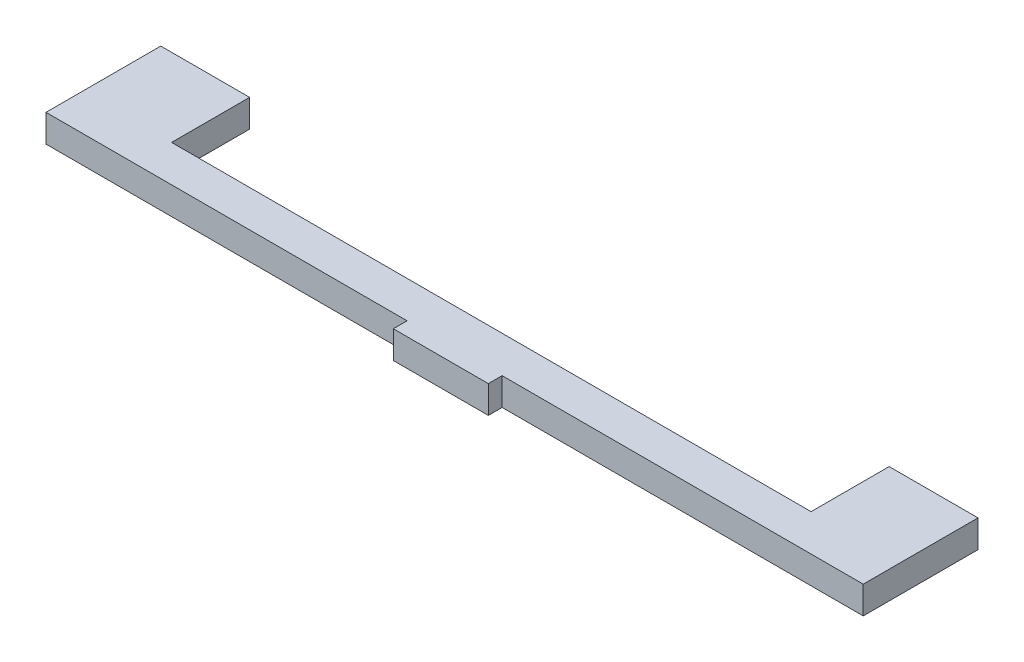
SolidWorks part; units mm, degrees
ref_plane "Front Plane" through (0, 0, 0) normal (0, 0, 1) x (1, 0, 0)
ref_plane "Top Plane" through (0, 0, 0) normal (0, 1, 0) x (1, 0, 0)
ref_plane "Right Plane" through (0, 0, 0) normal (1, 0, 0) x (0, 0, -1)
sketch "Sketch1" plane through (0, 0, 0) normal (0, 1, 0) x (1, 0, 0)
  line L0 (-9.9188, -12.9852) -> (10.7812, -12.9852)
  line L1 (10.7812, -12.9852) -> (10.7812, -9.9852)
  line L2 (10.7812, -9.9852) -> (89.4312, -9.9852)
  line L3 (89.4312, -9.9852) -> (89.4312, 15.0148)
  line L4 (89.4312, 15.0148) -> (70.0781, 15.0148)
  line L5 (70.0781, 15.0148) -> (70.0781, -1.9852)
  line L6 (70.0781, -1.9852) -> (-69.2156, -1.9852)
  line L7 (-69.2156, -1.9852) -> (-69.2156, 15.0148)
  line L8 (-69.2156, 15.0148) -> (-88.5688, 15.0148)
  line L9 (-88.5688, 15.0148) -> (-88.5688, -9.9852)
  line L10 (-88.5688, -9.9852) -> (-9.9188, -9.9852)
  line L11 (-9.9188, -9.9852) -> (-9.9188, -12.9852)
  point P10 (89.4312, 2.5148)
  dimension "D1" = 20.7
  dimension "D2" = 8
  dimension "D3" = 25
  dimension "D4" = 178
  dimension "D5" = 3
extrude "Boss-Extrude1" add sketch "Sketch1" along normal blind 6
